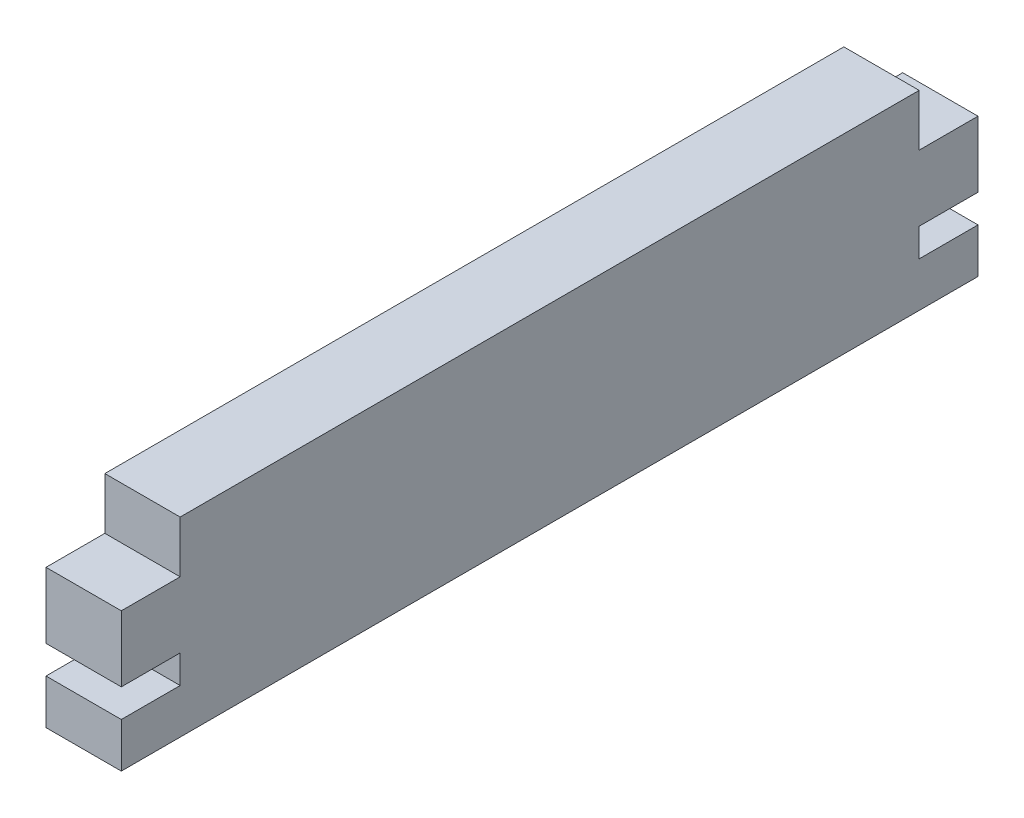
SolidWorks part; units mm, degrees
material "Maple"
ref_plane "Front Plane" through (0, 0, 0) normal (0, 0, 1) x (1, 0, 0)
ref_plane "Top Plane" through (0, 0, 0) normal (0, 1, 0) x (1, 0, 0)
ref_plane "Right Plane" through (0, 0, 0) normal (1, 0, 0) x (0, 0, -1)
sketch "Sketch1" plane through (0, 0, 0) normal (1, 0, 0) x (0, 0, -1)
  line L0 (25.4254, 0) -> (-25.4254, 0) construction
  line L1 (-12.7607, 0) -> (33.4673, 0)
  line L2 (-12.7607, 0) -> (-12.7607, 10.287)
  line L3 (-12.7607, 10.287) -> (33.4673, 10.287)
  line L4 (33.4673, 0) -> (33.4673, 10.287)
  line L5 (10.3533, 10.287) -> (10.3533, 0) construction
  line L6 (-12.7607, 10.287) -> (-9.5857, 10.287)
  line L7 (-12.7607, 10.287) -> (-12.7607, 7.493)
  line L8 (-12.7607, 7.493) -> (-9.5857, 7.493)
  line L9 (-9.5857, 10.287) -> (-9.5857, 7.493)
  line L10 (-12.7607, 3.937) -> (-9.5857, 3.937)
  line L11 (-12.7607, 3.937) -> (-12.7607, 2.413)
  line L12 (-12.7607, 2.413) -> (-9.5857, 2.413)
  line L13 (-9.5857, 3.937) -> (-9.5857, 2.413)
  line L14 (33.4673, 2.413) -> (30.2923, 2.413)
  line L15 (30.2923, 3.937) -> (30.2923, 2.413)
  line L16 (33.4673, 3.937) -> (30.2923, 3.937)
  line L17 (33.4673, 3.937) -> (33.4673, 2.413)
  line L18 (33.4673, 7.493) -> (30.2923, 7.493)
  line L19 (30.2923, 10.287) -> (30.2923, 7.493)
  line L20 (33.4673, 10.287) -> (30.2923, 10.287)
  line L21 (33.4673, 10.287) -> (33.4673, 7.493)
  dimension "D1" = 46.228
  dimension "D2" = 10.287
  dimension "D3" = 3.175
  dimension "D4" = 3.175
  dimension "D5" = 2.794
  dimension "D6" = 3.556
  dimension "D7" = 1.524
extrude "Boss-Extrude1" add sketch "Sketch1" along normal blind 4.064 contours L3 L5 L1 L4 L14 L15 L16 L18 L19 | L5 L3 L9 L8 L2 L10 L13 L12 L1
